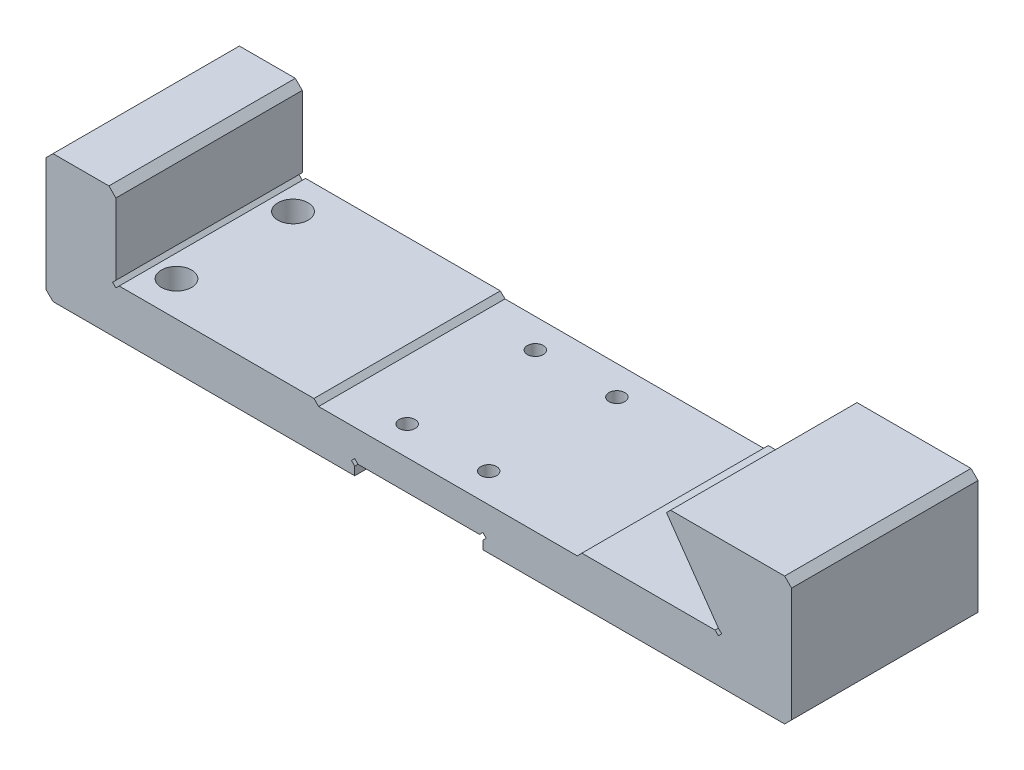
SolidWorks part; units mm, degrees
ref_plane "前视基准面" through (0, 0, 0) normal (0, 0, 1) x (1, 0, 0)
ref_plane "上视基准面" through (0, 0, 0) normal (0, 1, 0) x (1, 0, 0)
ref_plane "右视基准面" through (0, 0, 0) normal (1, 0, 0) x (0, 0, -1)
other "Configuration Table"
sketch "草图1" plane through (0, 0, 0) normal (0, 0, 1) x (1, 0, 0)
  line L0 (0, 54.1552) -> (0, -46.4686) construction
  line L5 (0, 0) -> (-43, 0)
  line L6 (-43, 0) -> (-45, 2)
  line L7 (-45, 2) -> (-128.5858, 2)
  line L8 (-128.5858, 2) -> (-130, 0.5858)
  line L9 (-130, 0.5858) -> (-131.4142, 2)
  line L10 (-131.4142, 2) -> (-130, 3.4142)
  line L11 (-130, 3.4142) -> (-130, 37)
  line L12 (-130, 37) -> (-160, 37)
  line L13 (-160, 37) -> (-160, -18)
  line L14 (-160, -18) -> (-27.5, -18)
  line L15 (0, 0) -> (68, 0)
  line L16 (68, 0) -> (70, 2)
  line L17 (70, 2) -> (127.1716, 2)
  line L18 (127.1716, 2) -> (128.5858, 0.5858)
  line L19 (128.5858, 0.5858) -> (130, 2)
  line L21 (105.0688, 37) -> (160, 37)
  line L22 (160, 37) -> (160, -18)
  line L23 (160, -18) -> (27.5, -18)
  line L24 (130, 2) -> (128.5858, 3.4142)
  line L25 (128.5858, 3.4142) -> (105.0688, 37)
  line L26 (-27.5, -18) -> (-27.5, -14.4142)
  line L27 (-27.5, -14.4142) -> (-28.9142, -13)
  line L28 (-28.9142, -13) -> (-27.5, -11.5858)
  line L29 (-27.5, -11.5858) -> (-26.0858, -13)
  line L30 (-26.0858, -13) -> (26.0858, -13)
  line L31 (27.5, -18) -> (27.5, -14.4142)
  line L32 (27.5, -11.5858) -> (26.0858, -13)
  line L33 (28.9142, -13) -> (27.5, -11.5858)
  line L34 (27.5, -14.4142) -> (28.9142, -13)
  point P29 (-26.7929, -12.2929)
  point P32 (26.7929, -12.2929)
  point P36 (0, -13)
  dimension "D1" = 2
  dimension "D2" = 2
  dimension "D3" = 2
  dimension "D4" = 135
  dimension "D5" = 260
  dimension "D6" = 320
  dimension "D7" = 85
  dimension "D8" = 55
  dimension "D9" = 2
  dimension "D10" = 2
  dimension "D11" = 2
  dimension "D12" = 130
  dimension "D13" = 2
  dimension "D14" = 35
  dimension "D15" = 135
  dimension "D16" = 55
  dimension "D17" = 60
  dimension "D18" = 55
  dimension "D19" = 30
  dimension "D20" = 2
  dimension "D21" = 15
  dimension "D22" = 2
  dimension "D23" = 2
  dimension "D24" = 2
  dimension "D25" = 135
  dimension "D26" = 27.5
extrude "凸台-拉伸1" add sketch "草图1" along normal mid plane 80
sketch "草图2" plane through (0, 2, 0) normal (0, 1, 0) x (1, 0, 0)
  line L0 (-130, -40) -> (-130, 40) construction
  line L2 (-45, -40) -> (-128.5858, -40) construction
  circle A0 centre (-119, 25) radius 6.5
  circle A1 centre (-119, -25) radius 6.5
  dimension "D1" = 13
  dimension "D2" = 13
  dimension "D3" = 50
  dimension "D5" = 8.5
  dimension "D4" = 11
extrude "切除-拉伸1" cut sketch "草图2" against normal blind 80
chamfer "倒角1" distance 3 angle 45 6 edges at (105.0688, 37, 0) (160, 37, 0) (160, -18, 0) (-160, -18, 0) (-130, 37, 0) (-160, 37, 0)
sketch "草图3" plane through (0, 0, 0) normal (0, 1, 0) x (1, 0, 0)
  line L1 (-17.5, 27.5) -> (17.5, 27.5)
  line L2 (-17.5, 27.5) -> (-17.5, -27.5)
  line L3 (-17.5, -27.5) -> (17.5, -27.5)
  line L4 (17.5, 27.5) -> (17.5, -27.5)
  line L5 (-17.5, 27.5) -> (17.5, -27.5) construction
  line L6 (-17.5, -27.5) -> (17.5, 27.5) construction
  point P0 (0, 0)
  dimension "D1" = 35
  dimension "D2" = 55
hole_wizard "M8 螺纹孔1" positions "3D草图1" profile "草图4" tap size "M8" standard "ISO"
sketch3d "3D草图1"
  point P0 (-17.5, 0, -27.5)
  point P3 (17.5, 0, -27.5)
  point P6 (17.5, 0, 27.5)
  point P9 (-17.5, 0, 27.5)
sketch "草图4" plane through (-17.5, 0, -27.5) normal (1, 0, 0) x (0, 0, 1)
  line L0 (0, 0) -> (0, 19.75)
  line L1 (0, 19.75) -> (3.4, 17.7071)
  line L2 (3.4, 17.7071) -> (3.4, 0)
  line L5 (3.4, 0) -> (0, 0)
  line L10 (0, 19.75) -> (-3.4, 17.7071) construction
  line L11 (0, -6.35) -> (0, 107.95) construction
  dimension "螺纹孔钻头直径" = 6.8
  dimension "螺纹孔钻头深度" = 19.75
  dimension "导头角度" = 118
cosmetic thread "孔螺纹线1" parameters "D1"=16, "D2"=8
cosmetic thread "孔螺纹线2" parameters "D1"=16, "D2"=8
cosmetic thread "孔螺纹线3" parameters "D1"=16, "D2"=8
cosmetic thread "孔螺纹线4" parameters "D1"=16, "D2"=8
